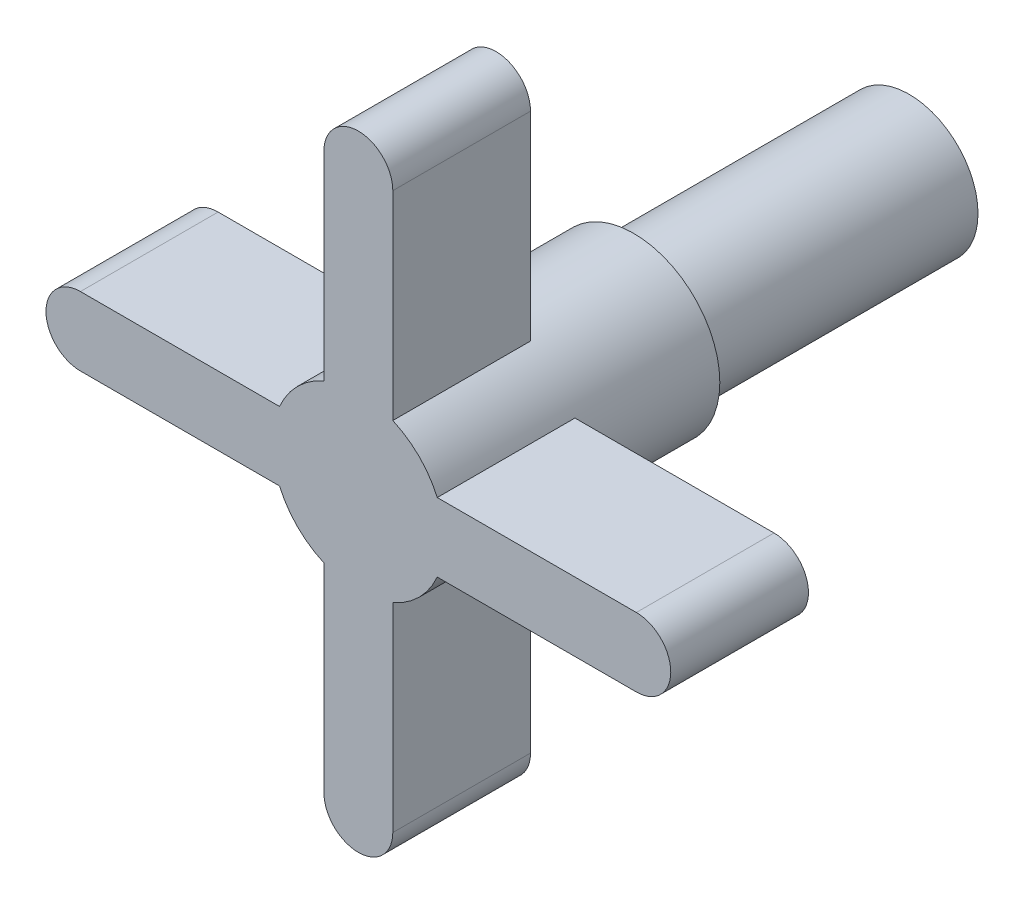
SolidWorks part; units mm, degrees
ref_plane "Front Plane" through (0, 0, 0) normal (0, 0, 1) x (1, 0, 0)
ref_plane "Top Plane" through (0, 0, 0) normal (0, 1, 0) x (1, 0, 0)
ref_plane "Right Plane" through (0, 0, 0) normal (1, 0, 0) x (0, 0, -1)
sketch "Sketch1" plane through (0, 0, 0) normal (0, 0, 1) x (1, 0, 0)
  line L11 (-40.3732, -5) -> (-5, -5)
  line L13 (5, -40.3732) -> (5, -5)
  line L15 (-5, -5) -> (-5, -40.3732)
  line L17 (-5, 5) -> (-40.3732, 5)
  line L18 (-5, 40.3732) -> (-5, 5)
  line L19 (5, 5) -> (5, 40.3732)
  line L20 (40.3732, 5) -> (5, 5)
  line L21 (5, -5) -> (40.3732, -5)
  arc A5 (-5, -40.3732) -> (5, -40.3732) centre (0, -40.3732) ccw
  arc A6 (-40.3732, 5) -> (-40.3732, -5) centre (-40.3732, 0) ccw
  arc A7 (5, 40.3732) -> (-5, 40.3732) centre (0, 40.3732) ccw
  arc A8 (40.3732, -5) -> (40.3732, 5) centre (40.3732, 0) ccw
  dimension "D1" = 4
extrude "Boss-Extrude1" add sketch "Sketch1" along normal blind 20
sketch "Sketch2" plane through (0, 0, 20) normal (0, 0, 1) x (1, 0, 0)
  circle A0 centre (0, 0) radius 10
extrude "Boss-Extrude2" add sketch "Sketch2" against normal blind 80
sketch "Sketch3" plane through (0, 0, 20) normal (0, 0, 1) x (1, 0, 0)
  circle A0 centre (0, 0) radius 12.5
extrude "Boss-Extrude3" add sketch "Sketch3" against normal blind 40
